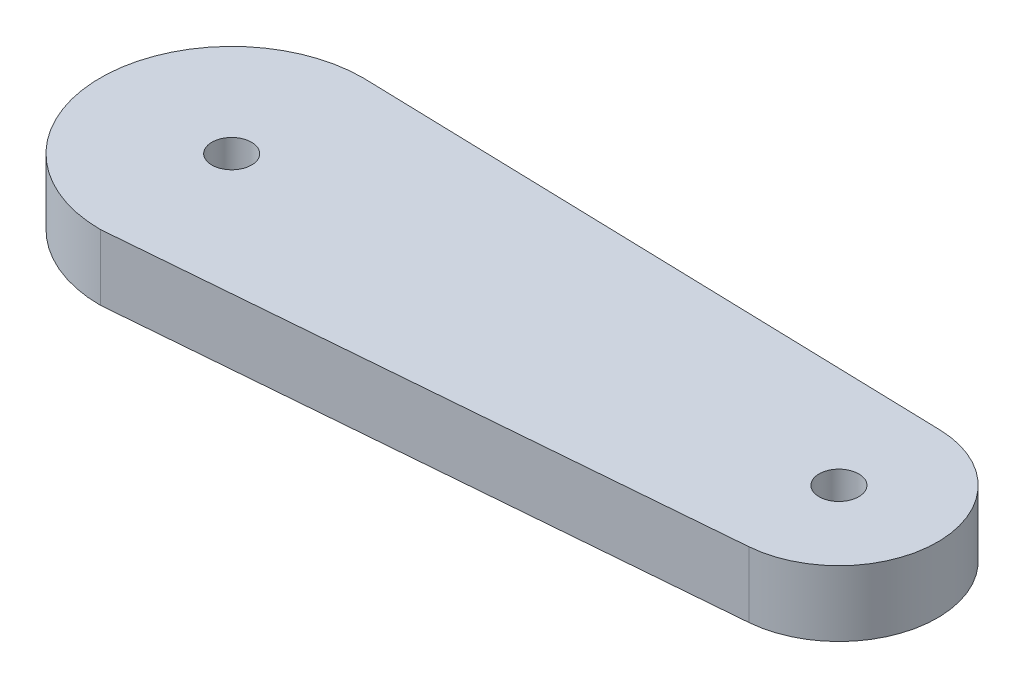
SolidWorks part; units mm, degrees
ref_plane "Front Plane" through (0, 0, 0) normal (0, 0, 1) x (1, 0, 0)
ref_plane "Top Plane" through (0, 0, 0) normal (0, 1, 0) x (1, 0, 0)
ref_plane "Right Plane" through (0, 0, 0) normal (1, 0, 0) x (0, 0, -1)
sketch "Sketch1" plane through (0, 0, 0) normal (0, 1, 0) x (1, 0, 0)
  line L0 (0, 10) -> (45.1912, 8.7436)
  line L1 (0, -10) -> (45.601, -6.2279)
  circle A0 centre (0, 0) radius 10
  circle A1 centre (44.9827, 1.2465) radius 7.5
  dimension "D2" = 20
  dimension "D3" = 15
  dimension "D1" = 45
extrude "Boss-Extrude1" add sketch "Sketch1" along normal blind 5 contours L1 A0 L0 | A1 L0 A0 L1 | A1 L1
sketch "Sketch2" plane through (0, 5, 0) normal (0, 1, 0) x (1, 0, 0)
  circle A0 centre (0, 0) radius 1.51
  circle A1 centre (44.9827, 1.2465) radius 1.51
  dimension "D1" = 3.02
  dimension "D2" = 3.02
extrude "Cut-Extrude1" cut sketch "Sketch2" against normal up to next
